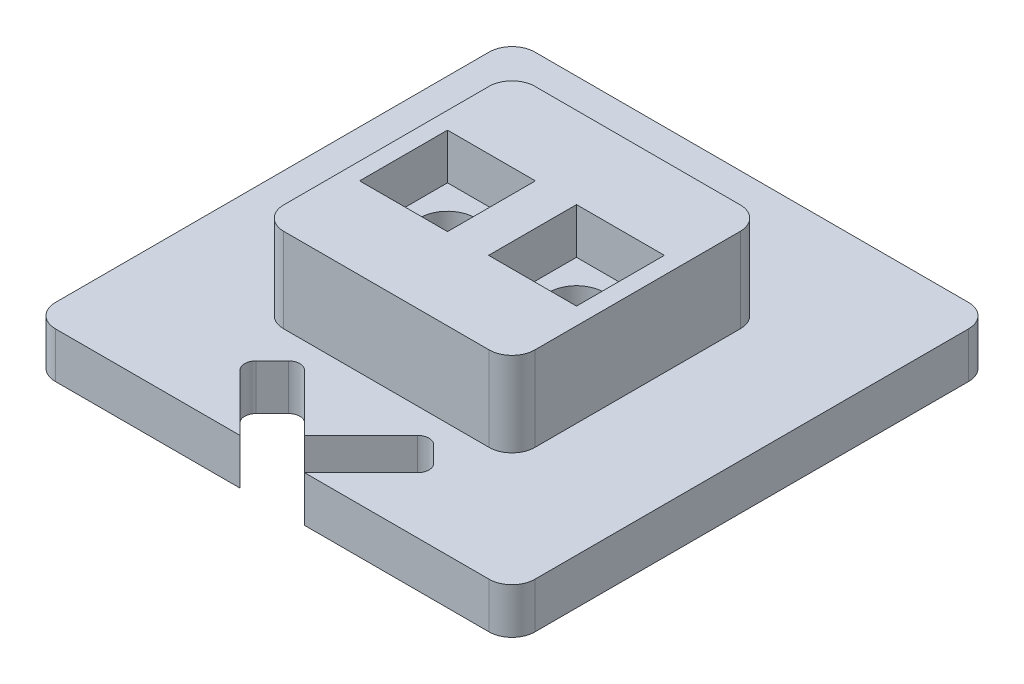
SolidWorks part; units mm, degrees
ref_plane "Front Plane" through (0, 0, 0) normal (0, 0, 1) x (1, 0, 0)
ref_plane "Top Plane" through (0, 0, 0) normal (0, 1, 0) x (1, 0, 0)
ref_plane "Right Plane" through (0, 0, 0) normal (1, 0, 0) x (0, 0, -1)
sketch "Sketch1" plane through (0, 0, 0) normal (0, 1, 0) x (1, 0, 0)
  line L1 (-5.5, -5.5) -> (5.5, -5.5)
  line L2 (-5.5, -5.5) -> (-5.5, 5.5)
  line L3 (-5.5, 5.5) -> (5.5, 5.5)
  line L4 (5.5, -5.5) -> (5.5, 5.5)
  line L5 (-5.5, -5.5) -> (5.5, 5.5) construction
  line L6 (-5.5, 5.5) -> (5.5, -5.5) construction
  point P0 (0, 0)
  dimension "D1" = 11
  dimension "D2" = 11
extrude "Boss-Extrude1" add sketch "Sketch1" along normal blind 3.7
fillet "Fillet1" radius 1 4 edges at (-5.5, 1.85, -5.5) (-5.5, 1.85, 5.5) (5.5, 1.85, -5.5) (5.5, 1.85, 5.5)
sketch "Sketch2" plane through (0, 3.7, 0) normal (0, 1, 0) x (1, 0, 0)
  line L0 (-2.825, 0) -> (2.825, 0) construction
  line L2 (-4.75, -1.925) -> (-0.9, -1.925)
  line L3 (-4.75, -1.925) -> (-4.75, 1.925)
  line L4 (-4.75, 1.925) -> (-0.9, 1.925)
  line L5 (-0.9, -1.925) -> (-0.9, 1.925)
  line L6 (-4.75, -1.925) -> (-0.9, 1.925) construction
  line L7 (-4.75, 1.925) -> (-0.9, -1.925) construction
  line L8 (0.9, -1.925) -> (4.75, -1.925)
  line L9 (0.9, -1.925) -> (0.9, 1.925)
  line L10 (0.9, 1.925) -> (4.75, 1.925)
  line L11 (4.75, -1.925) -> (4.75, 1.925)
  line L12 (0.9, -1.925) -> (4.75, 1.925) construction
  line L13 (0.9, 1.925) -> (4.75, -1.925) construction
  point P4 (0, 0)
  dimension "D1" = 3.85
  dimension "D2" = 3.85
  dimension "D3" = 3.85
  dimension "D4" = 3.85
  dimension "D5" = 5.65
extrude "Cut-Extrude1" cut sketch "Sketch2" against normal blind 2
sketch "Sketch4" plane through (0, 0, 0) normal (0, -1, 0) x (-1, 0, 0)
  line L0 (2.825, 0) -> (-2.825, 0) construction
  circle A0 centre (2.825, 0) radius 2.2
  circle A1 centre (-2.825, 0) radius 2.2
  point P8 (0, 0)
  dimension "D1" = 5.65
  dimension "D2" = 4.4
  dimension "D3" = 4.4
extrude "Boss-Extrude2" add sketch "Sketch4" along normal blind 2
sketch "Sketch5" plane through (0, -2, 0) normal (0, -1, 0) x (-1, 0, 0)
  line L1 (9.5, 10.5) -> (-9.5, 10.5)
  line L2 (10.5, 9.5) -> (10.5, -9.5)
  line L3 (9.5, -10.5) -> (-9.5, -10.5)
  line L4 (-10.5, 9.5) -> (-10.5, -9.5)
  line L5 (10.5, 10.5) -> (-10.5, -10.5) construction
  line L6 (10.5, -10.5) -> (-10.5, 10.5) construction
  arc A0 (10.5, -9.5) -> (9.5, -10.5) centre (9.5, -9.5) cw
  arc A1 (-10.5, -9.5) -> (-9.5, -10.5) centre (-9.5, -9.5) ccw
  arc A2 (-9.5, 10.5) -> (-10.5, 9.5) centre (-9.5, 9.5) ccw
  arc A3 (9.5, 10.5) -> (10.5, 9.5) centre (9.5, 9.5) cw
  point P0 (0, 0)
  dimension "D3" = 1
  dimension "D1" = 21
  dimension "D2" = 21
extrude "Boss-Extrude3" add sketch "Sketch5" against normal blind 2
sketch "Sketch3" plane through (0, 3.7, 0) normal (0, 1, 0) x (1, 0, 0)
  line L0 (-2.825, 0) -> (2.825, 0) construction
  circle A0 centre (-2.825, 0) radius 1.2
  circle A1 centre (2.825, 0) radius 1.2
  point P8 (0, 0)
  dimension "D2" = 2.4
  dimension "D3" = 2.4
  dimension "D1" = 5.65
extrude "Cut-Extrude2" cut sketch "Sketch3" against normal through all
sketch "Sketch7" plane through (0, 0, 0) normal (0, 1, 0) x (1, 0, 0)
  line L0 (9.5, -10.5) -> (-9.5, -10.5) construction
  line L1 (2.8284, -14.7426) -> (4.2426, -13.3284)
  line L2 (2.8284, -14.7426) -> (-3.8891, -8.0251)
  line L3 (-3.8891, -7.318) -> (-3.182, -6.6109)
  line L4 (4.2426, -13.3284) -> (-2.4749, -6.6109)
  line L5 (2.8284, -14.7426) -> (-2.8284, -6.2574) construction
  line L6 (-4.2426, -7.6716) -> (4.2426, -13.3284) construction
  line L8 (-4.2426, -13.3284) -> (-2.8284, -14.7426)
  line L9 (-4.2426, -13.3284) -> (2.4749, -6.6109)
  line L10 (3.182, -6.6109) -> (3.8891, -7.318)
  line L11 (-2.8284, -14.7426) -> (3.8891, -8.0251)
  line L12 (-4.2426, -13.3284) -> (4.2426, -7.6716) construction
  line L13 (2.8284, -6.2574) -> (-2.8284, -14.7426) construction
  arc A0 (-2.4749, -6.6109) -> (-3.182, -6.6109) centre (-2.8284, -6.9645) ccw
  arc A1 (3.8891, -7.318) -> (3.8891, -8.0251) centre (3.5355, -7.6716) cw
  arc A2 (3.182, -6.6109) -> (2.4749, -6.6109) centre (2.8284, -6.9645) ccw
  arc A3 (-3.8891, -7.318) -> (-3.8891, -8.0251) centre (-3.5355, -7.6716) ccw
  point P0 (0, -10.5)
  point P7 (0, -10.5)
  point P12 (-1.4142, -10.5)
  point P13 (1.4142, -10.5)
  line M12 (-9.5, -10.5) -> (9.5, -10.5)
  dimension "D7" = 0.5
  dimension "D8" = 0.5
  dimension "D1" = 2
  dimension "D2" = 45
  dimension "D3" = 2
  dimension "D4" = 45
  dimension "D5" = 4
  dimension "D6" = 4
extrude "Cut-Extrude3" cut sketch "Sketch7" against normal through all contours L10 A2 L9 L4 L11 A1 | L3 A3 L2 L9 L4 A0 | L9 L4 M12
sketch "Sketch8" plane through (0, -2, 0) normal (0, -1, 0) x (1, 0, 0)
  circle A0 centre (-2.825, 0) radius 1.2
  circle A1 centre (-2.825, 0) radius 2.2
  circle A2 centre (2.825, 0) radius 1.2
  circle A3 centre (2.825, 0) radius 2.2
  dimension "D1" = 1
  dimension "D2" = 1
extrude "Boss-Extrude4" add sketch "Sketch8" along normal blind 4
equation "\"D2@Sketch2\"=\"D1@Sketch2\""
equation "\"D3@Sketch2\"=\"D1@Sketch2\""
equation "\"D4@Sketch2\"=\"D1@Sketch2\""
equation "\"D2@Sketch1\"=\"D1@Sketch1\""
equation "\"D3@Sketch3\"=\"D2@Sketch3\""
equation "\"D3@Sketch4\"=\"D2@Sketch4\""
equation "\"D2@Sketch5\"=\"D1@Sketch5\""
equation "\"D3@Sketch7\"=\"D1@Sketch7\""
equation "\"D6@Sketch7\"=\"D5@Sketch7\""
equation "\"D2@Sketch8\"=\"D1@Sketch8\""
